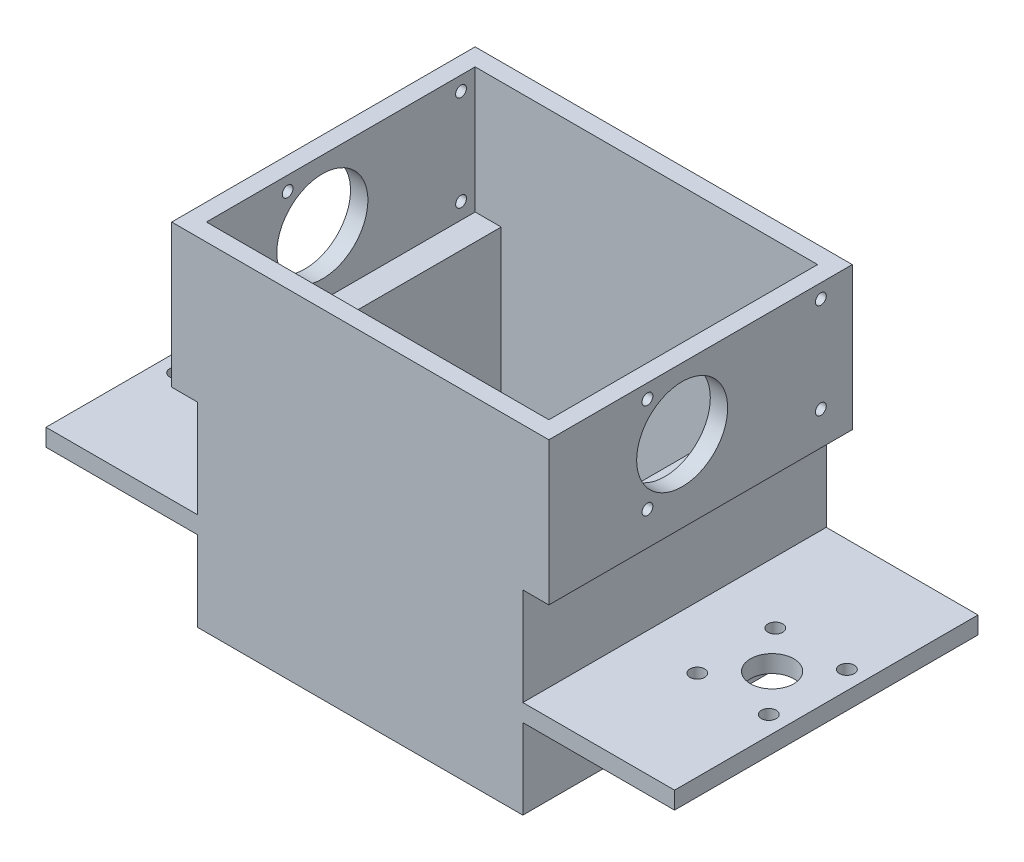
SolidWorks part; units mm, degrees
ref_plane "Front Plane" through (0, 0, 0) normal (0, 0, 1) x (1, 0, 0)
ref_plane "Top Plane" through (0, 0, 0) normal (0, 1, 0) x (1, 0, 0)
ref_plane "Right Plane" through (0, 0, 0) normal (1, 0, 0) x (0, 0, -1)
sketch "Sketch1" plane through (0, 0, 0) normal (0, 1, 0) x (1, 0, 0)
  line L0 (0, 0) -> (0, -14.43) construction
  line L1 (-37.5, 20) -> (37.5, 20)
  line L2 (-37.5, 20) -> (-37.5, -20)
  line L3 (-37.5, -20) -> (37.5, -20)
  line L4 (37.5, 20) -> (37.5, -20)
  line L5 (-37.5, 20) -> (37.5, -20) construction
  line L6 (-37.5, -20) -> (37.5, 20) construction
  line L7 (0, 0) -> (6.508, 0) construction
  line L8 (-2.5, 10) -> (2.5, 10)
  line L9 (-2.5, 10) -> (-2.5, -10)
  line L10 (-2.5, -10) -> (2.5, -10)
  line L11 (2.5, 10) -> (2.5, -10)
  line L12 (-2.5, 10) -> (2.5, -10) construction
  line L13 (-2.5, -10) -> (2.5, 10) construction
  circle A0 centre (-21, 0) radius 5
  circle A1 centre (-30, 8.25) radius 1.7
  circle A2 centre (-12, 8.25) radius 1.7
  circle A3 centre (-12, -8.25) radius 1.7
  circle A4 centre (-30, -8.25) radius 1.7
  circle A5 centre (12, 8.25) radius 1.7
  circle A6 centre (12, -8.25) radius 1.7
  circle A7 centre (21, 0) radius 5
  circle A8 centre (30, -8.25) radius 1.7
  circle A9 centre (30, 8.25) radius 1.7
  circle A10 centre (-30, -17.5) radius 1.1976
  circle A11 centre (-13.5, -17.5) radius 1.1976
  circle A12 centre (13.5, -17.5) radius 1.1976
  circle A13 centre (30, -17.5) radius 1.1976
  circle A14 centre (30, 17.5) radius 1.1976
  circle A15 centre (13.5, 17.5) radius 1.1976
  circle A16 centre (-13.5, 17.5) radius 1.1976
  circle A17 centre (-30, 17.5) radius 1.1976
  point P0 (0, 0)
  dimension "D3" = 10
  dimension "D4" = 21
  dimension "D5" = 8.25
  dimension "D6" = 9
  dimension "D9" = 5
  dimension "D11" = 20
  dimension "D12" = 7.5
  dimension "D13" = 25.5
  dimension "D14" = 7.5
  dimension "D15" = 2.5
  dimension "D17" = 16.5
  dimension "D18" = 16.5
  dimension "D1" = 75
  dimension "D2" = 40
  dimension "D10" = 20
  dimension "D7" = 2
  dimension "D8" = 2
  dimension "D16" = 2
extrude "Boss-Extrude1" add sketch "Sketch1" along normal blind 3
sketch "Sketch2" plane through (0, 3, 0) normal (0, 1, 0) x (1, 0, 0)
  line L0 (-37.5, 20) -> (-37.5, -20) construction
  line L1 (-33.5, 14) -> (33.5, 14)
  line L2 (-33.5, 14) -> (-33.5, -14)
  line L3 (-33.5, -14) -> (33.5, -14)
  line L4 (33.5, 14) -> (33.5, -14)
  line L5 (37.5, -20) -> (37.5, 20) construction
  line L6 (37.5, 20) -> (-37.5, 20) construction
  line L7 (-37.5, -20) -> (37.5, -20) construction
  dimension "D1" = 4
  dimension "D2" = 4
  dimension "D3" = 6
  dimension "D4" = 6
extrude "Cut-Extrude1" cut sketch "Sketch2" against normal through all both and the other way through all
sketch "Sketch3" plane through (0, 3, 0) normal (0, 1, 0) x (1, 0, 0)
  line L1 (37.5, 20) -> (-37.5, 20)
  line L2 (37.5, 20) -> (37.5, 35)
  line L3 (37.5, 35) -> (-37.5, 35)
  line L4 (-37.5, 20) -> (-37.5, 35)
  line L5 (-37.5, -20) -> (37.5, -20)
  line L6 (-37.5, -20) -> (-37.5, -35)
  line L7 (-37.5, -35) -> (37.5, -35)
  line L8 (37.5, -20) -> (37.5, -35)
  line L10 (-37.5, 20) -> (-33.5, 20)
  line L11 (-37.5, 20) -> (-37.5, -20)
  line L12 (-37.5, -20) -> (-33.5, -20)
  line L13 (-33.5, 20) -> (-33.5, -20)
  line L14 (37.5, 20) -> (33.5, 20)
  line L15 (37.5, 20) -> (37.5, -20)
  line L16 (37.5, -20) -> (33.5, -20)
  line L17 (33.5, 20) -> (33.5, -20)
  line M3 (-33.5, -14) -> (-33.5, 14)
  line M5 (33.5, 14) -> (33.5, -14)
  line M11 (37.5, -20) -> (37.5, 20)
  line M12 (37.5, 20) -> (-37.5, 20)
  line M13 (-37.5, 20) -> (-37.5, -20)
  line M14 (-37.5, -20) -> (37.5, -20)
  dimension "D1" = 15
  dimension "D2" = 15
extrude "Boss-Extrude3" add sketch "Sketch3" along normal blind 75 and the other way blind 3 contours L8 L5 L6 L7 M14 | L4 L1 L2 L3 M12 | L17 M12 M5 M14 M11 | L13 L1 M13 M14 M3
sketch "Sketch6" plane through (0, 3, 0) normal (0, 1, 0) x (1, 0, 0)
  line L0 (-37.5, -35) -> (37.5, -35) construction
  line L1 (-33.5, -20) -> (33.5, -20)
  line L2 (-33.5, -20) -> (-33.5, -31)
  line L3 (-33.5, -31) -> (33.5, -31)
  line L4 (33.5, -20) -> (33.5, -31)
  line L5 (33.5, 20) -> (-33.5, 20)
  line L6 (33.5, 20) -> (33.5, 31)
  line L7 (33.5, 31) -> (-33.5, 31)
  line L8 (-33.5, 20) -> (-33.5, 31)
  line L9 (37.5, 35) -> (-37.5, 35) construction
  dimension "D1" = 4
  dimension "D2" = 4
extrude "Cut-Extrude4" cut sketch "Sketch6" along normal through all
sketch "Sketch7" plane through (-37.5, 0, 0) normal (-1, 0, 0) x (0, 0, 1)
  line L0 (35, 0) -> (35, 78) construction
  line L1 (-35, 78) -> (35, 78)
  line L2 (-35, 78) -> (-35, 41)
  line L3 (-35, 41) -> (35, 41)
  line L4 (35, 78) -> (35, 41)
  dimension "D1" = 37
extrude "Boss-Extrude4" add sketch "Sketch7" along normal blind 6
ref_plane "Plane1" through (0, 0, 0) normal (1, 0, 0) x (0, 0, -1)
mirror "Mirror2" about plane through (0, 0, 0) normal (1, 0, 0) of "Boss-Extrude4"
sketch "Sketch8" plane through (0, 78, 0) normal (0, 1, 0) x (1, 0, 0)
  line L0 (-43.5, -35) -> (-43.5, 35) construction
  line L1 (-33.5, 31) -> (-39.5, 31)
  line L2 (-33.5, 31) -> (-33.5, -31)
  line L3 (-33.5, -31) -> (-39.5, -31)
  line L4 (-39.5, 31) -> (-39.5, -31)
  line L5 (33.5, -31) -> (39.5, -31)
  line L6 (33.5, -31) -> (33.5, 31)
  line L7 (33.5, 31) -> (39.5, 31)
  line L8 (39.5, -31) -> (39.5, 31)
  line L9 (43.5, -35) -> (43.5, 35) construction
  dimension "D1" = 4
  dimension "D2" = 4
extrude "Cut-Extrude6" cut sketch "Sketch8" against normal blind 29
sketch "Sketch9" plane through (-43.5, 0, 0) normal (-1, 0, 0) x (0, 0, 1)
  line L0 (35, 78) -> (-35, 78) construction
  line L2 (15.5, 49.5) -> (-31, 49.5)
  line L3 (15.5, 49.5) -> (15.5, 78)
  line L4 (15.5, 78) -> (-31, 78)
  line L5 (-31, 49.5) -> (-31, 78)
  line L6 (-31, 49) -> (-31, 78) construction
  circle A0 centre (4.25, 63.75) radius 10.5
  circle A1 centre (12.25, 74.75) radius 1.25
  circle A2 centre (-27.75, 74.75) radius 1.25
  circle A3 centre (-27.75, 52.75) radius 1.25
  circle A4 centre (12.25, 52.75) radius 1.25
  dimension "D1" = 14.25
  dimension "D2" = 21
  dimension "D3" = 2.5
  dimension "D4" = 3.25
  dimension "D5" = 8
  dimension "D11" = 3.25
  dimension "D8" = 28.5
  dimension "D9" = 46.5
  dimension "D10" = 0
  dimension "D6" = 2
  dimension "D7" = 2
extrude "Cut-Extrude8" cut sketch "Sketch9" against normal through all contours A2 | A3 | A0 | A4 | A1
sketch "Sketch11" plane through (0, 0, 35) normal (0, 0, 1) x (1, 0, 0)
  line L0 (43.5, 41) -> (43.5, 78) construction
  line L1 (-43.5, 41) -> (-37.5, 41)
  line L2 (-43.5, 41) -> (-43.5, 45)
  line L3 (-43.5, 45) -> (-37.5, 45)
  line L4 (-37.5, 41) -> (-37.5, 45)
  line L5 (37.5, 41) -> (43.5, 41)
  line L6 (37.5, 41) -> (37.5, 45)
  line L7 (37.5, 45) -> (43.5, 45)
  line L8 (43.5, 41) -> (43.5, 45)
  line L11 (-39.5, 49) -> (-33.5, 49) construction
  line L12 (33.5, 49) -> (39.5, 49) construction
  dimension "D1" = 4
  dimension "D2" = 4
extrude "Cut-Extrude9" cut sketch "Sketch11" against normal through all
sketch "Sketch12" plane through (0, 0, 35) normal (0, 0, 1) x (1, 0, 0)
  line L0 (-37.5, 0) -> (-37.5, 45) construction
  line L1 (-37.5, 18.5) -> (-72.5, 18.5)
  line L2 (-37.5, 18.5) -> (-37.5, -28)
  line L3 (-37.5, -28) -> (-72.5, -28)
  line L4 (-72.5, 18.5) -> (-72.5, -28)
  line L5 (-37.5, 0) -> (37.5, 0) construction
  line L7 (-72.5, 18.5) -> (-37.5, 18.5)
  line L8 (-72.5, 18.5) -> (-72.5, 22.5)
  line L9 (-72.5, 22.5) -> (-37.5, 22.5)
  line L10 (-37.5, 18.5) -> (-37.5, 22.5)
  circle A0 centre (-51.75, -16.75) radius 10.25
  line M6 (-37.5, 45) -> (-37.5, 0)
  dimension "D3" = 11.25
  dimension "D4" = 20.5
  dimension "D7" = 14.25
  dimension "D1" = 35
  dimension "D2" = 46.5
  dimension "D5" = 28
  dimension "D6" = 4
extrude "Boss-Extrude5" add sketch "Sketch12" against normal blind 70 contours L9 L8 L1 M6
mirror "Mirror3" about plane through (0, 0, 0) normal (1, 0, 0) of "Boss-Extrude5"
sketch "Sketch13" plane through (0, 22.5, 0) normal (0, 1, 0) x (1, 0, 0)
  line L0 (0, 0) -> (0, -7.8878) construction
  line L8 (-72.5, -35) -> (-37.5, -35) construction
  line L10 (-72.5, 35) -> (-72.5, -35) construction
  circle A15 centre (-60, 0) radius 5
  circle A16 centre (-68.25, 9) radius 1.7
  circle A17 centre (-51.75, 9) radius 1.7
  circle A18 centre (-51.75, -9) radius 1.7
  circle A19 centre (-68.25, -9) radius 1.7
  circle A20 centre (68.25, -9) radius 1.7
  circle A21 centre (51.75, -9) radius 1.7
  circle A22 centre (51.75, 9) radius 1.7
  circle A23 centre (68.25, 9) radius 1.7
  circle A24 centre (60, 0) radius 5
  dimension "D1" = 35
  dimension "D2" = 12.5
  dimension "D3" = 4.25
  dimension "D4" = 9
  dimension "D5" = 2
  dimension "D6" = 2
extrude "Cut-Extrude11" cut sketch "Sketch13" against normal blind 10
